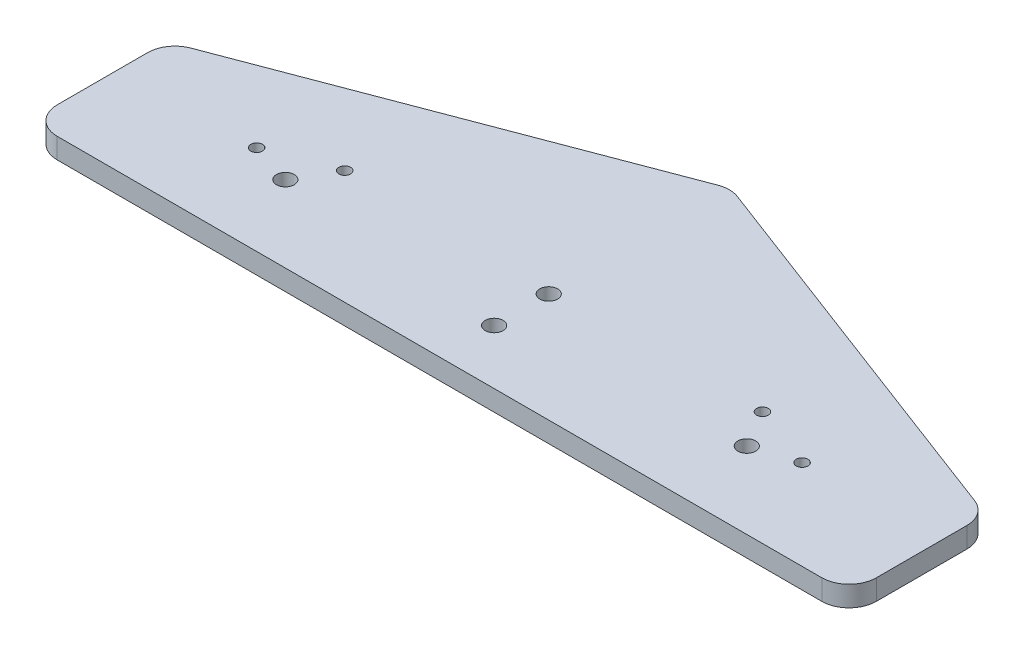
SolidWorks part; units mm, degrees
ref_plane "Front Plane" through (0, 0, 0) normal (0, 0, 1) x (1, 0, 0)
ref_plane "Top Plane" through (0, 0, 0) normal (0, 1, 0) x (1, 0, 0)
ref_plane "Right Plane" through (0, 0, 0) normal (1, 0, 0) x (0, 0, -1)
sketch "Sketch2" plane through (0, 0, 0) normal (0, 1, 0) x (1, 0, 0)
  line L0 (0, 0) -> (140, 0)
  line L1 (150, 10) -> (150, 43.095)
  line L2 (143.5429, 52.4464) -> (3.5429, 105.4876)
  line L3 (-3.5429, 105.4876) -> (-143.5429, 52.4464)
  line L4 (-150, 43.095) -> (-150, 10)
  line L5 (-140, 0) -> (0, 0)
  line L6 (-100, 68.9433) -> (0, 106.8299) construction
  line L7 (0, 106.8299) -> (100, 68.9433) construction
  line L8 (100, 68.9433) -> (84.4998, 28.0311) construction
  line L9 (-100, 68.9433) -> (-84.4998, 28.0311) construction
  line L10 (-88.0427, 37.3825) -> (-76.3535, 41.8111) construction
  line L11 (-88.0427, 37.3825) -> (-99.7319, 32.9539) construction
  line L12 (76.3535, 41.8111) -> (88.0427, 37.3825) construction
  line L13 (88.0427, 37.3825) -> (99.7319, 32.9539) construction
  arc A0 (150, 43.095) -> (143.5429, 52.4464) centre (140, 43.095) ccw
  arc A1 (140, 0) -> (150, 10) centre (140, 10) ccw
  arc A2 (-150, 10) -> (-140, 0) centre (-140, 10) ccw
  arc A3 (-143.5429, 52.4464) -> (-150, 43.095) centre (-140, 43.095) ccw
  arc A4 (3.5429, 105.4876) -> (-3.5429, 105.4876) centre (0, 96.1363) ccw
  point P18 (150, 50)
  point P21 (150, 0)
  point P24 (-150, 0)
  point P27 (-150, 50)
  point P30 (0, 106.8299)
  point P33 (0, 125.7732)
  point P34 (0, 0)
  dimension "D9" = 10
  dimension "D1" = 150
  dimension "D2" = 150
  dimension "D3" = 50
  dimension "D4" = 50
  dimension "D5" = 138.5
  dimension "D6" = 150
  dimension "D7" = 200
  dimension "D8" = 43.75
  dimension "D10" = 43.75
  dimension "D11" = 33.75
  dimension "D12" = 12.5
  dimension "D13" = 12.5
  dimension "D14" = 33.75
  dimension "D15" = 12.5
  dimension "D16" = 12.5
extrude "Boss-Extrude1" add sketch "Sketch2" against normal blind 7.5 contours L3 A3 L4 A2 L5 L0 A1 L1 A0 L2 A4
hole_wizard "1/4 Clearance Hole4" positions "Sketch11" profile "Sketch12" hole size "1/4" standard "ANSI Inch" end condition through all
sketch "Sketch11" plane through (0, 0, 0) normal (0, 1, 0) x (1, 0, 0)
  line L0 (143.5429, 52.4464) -> (3.5429, 105.4876) construction
  line L1 (-3.5429, 105.4876) -> (-143.5429, 52.4464) construction
  line L2 (-100, 68.9433) -> (100, 68.9433) construction
  line L3 (100, 68.9433) -> (84.4998, 28.0311) construction
  line L4 (84.4998, 28.0311) -> (-84.4998, 28.0311) construction
  line L5 (-84.4998, 28.0311) -> (-100, 68.9433) construction
  line L6 (-140, 0) -> (140, 0) construction
  point P0 (84.4998, 28.0311)
  point P2 (-84.4998, 28.0311)
  point P19 (0, 40)
  point P21 (0, 20)
  dimension "D1" = 20
  dimension "D2" = 40
  dimension "D4" = 90
  dimension "D5" = 200
  dimension "D6" = 90
  dimension "D7" = 100
  dimension "D8" = 43.75
sketch "Sketch12" plane through (84.4998, 0, -28.0311) normal (1, 0, 0) x (0, 0, 1)
  line L0 (0, 0) -> (0, 7.5)
  line L1 (0, 7.5) -> (3.2639, 7.5)
  line L2 (3.2639, 7.5) -> (3.2639, 0)
  line L5 (3.2639, 0) -> (0, 0)
  line L11 (0, -6.35) -> (0, 107.95) construction
  dimension "Thru Hole Dia." = 6.5278
  dimension "Thru Hole Depth" = 7.5
hole_wizard "M4 Clearance Hole1" positions "Sketch13" profile "Sketch14" hole size "M4" standard "ANSI Metric" end condition through all
sketch "Sketch13" plane through (0, 0, 0) normal (0, 1, 0) x (1, 0, 0)
  line L0 (-3.5429, 105.4876) -> (-143.5429, 52.4464) construction
  line L1 (143.5429, 52.4464) -> (3.5429, 105.4876) construction
  line L2 (-100, 68.9433) -> (100, 68.9433) construction
  line L9 (-100, 68.9433) -> (-88.1805, 37.3306) construction
  line L10 (-88.1805, 37.3306) -> (88.1805, 37.3306) construction
  line L11 (88.1805, 37.3306) -> (100, 68.9433) construction
  point P0 (-76.4912, 41.759)
  point P2 (-99.8696, 32.9017)
  point P4 (76.4912, 41.759)
  point P6 (99.8696, 32.9017)
  dimension "D1" = 200
  dimension "D2" = 12.5
  dimension "D3" = 33.75
  dimension "D4" = 33.75
  dimension "D5" = 33.75
  dimension "D6" = 33.75
  dimension "D7" = 100
  dimension "D8" = 69.5
  dimension "D9" = 69.5
  dimension "D10" = 33.75
  dimension "D11" = 12.5
  dimension "D12" = 12.5
  dimension "D13" = 12.5
sketch "Sketch14" plane through (-76.4912, 0, -41.759) normal (1, 0, 0) x (0, 0, 1)
  line L0 (0, 0) -> (0, 7.5)
  line L1 (0, 7.5) -> (2.15, 7.5)
  line L2 (2.15, 7.5) -> (2.15, 0)
  line L5 (2.15, 0) -> (0, 0)
  line L11 (0, -6.35) -> (0, 107.95) construction
  dimension "Thru Hole Dia." = 4.3
  dimension "Thru Hole Depth" = 7.5
